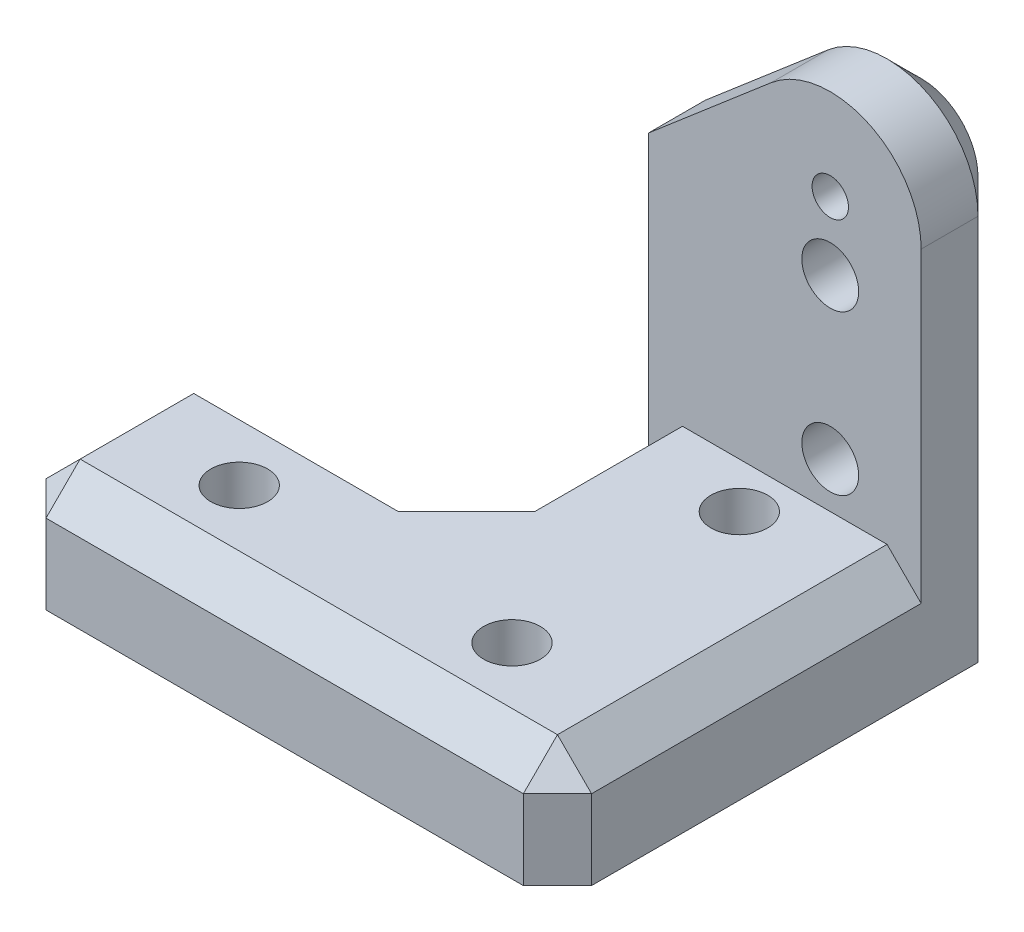
SolidWorks part; units mm, degrees
ref_plane "Plano frontal" through (0, 0, 0) normal (0, 0, 1) x (1, 0, 0)
ref_plane "Plano superior" through (0, 0, 0) normal (0, 1, 0) x (1, 0, 0)
ref_plane "Plano direito" through (0, 0, 0) normal (1, 0, 0) x (0, 0, -1)
sketch "Esboço1" plane through (0, 0, 0) normal (0, 0, 1) x (1, 0, 0)
  line L0 (0, 0) -> (0, 12)
  line L1 (0, 12) -> (9.4001, 20.0398)
  line L4 (16, 17) -> (16, 4)
  line L5 (16, 4) -> (16, 0)
  line L6 (16, 0) -> (0, 0)
  arc A0 (9.4001, 20.0398) -> (16, 17) centre (12, 17) cw
  point P19 (12, 17)
  dimension "D1" = 4
  dimension "D2" = 16
  dimension "D3" = 12
  dimension "D4" = 16
  dimension "D5" = 4
  dimension "D6" = 17
extrude "Ressalto-extrusão1" add sketch "Esboço1" along normal blind 20
sketch "Esboço2" plane through (0, 0, 0) normal (-1, 0, 0) x (0, 0, 1)
  line L0 (0, 0) -> (0, 5) construction
  line L1 (0, 5) -> (20, 5) construction
  line L3 (20, 21) -> (0, 21) construction
  line L4 (20, 5) -> (4, 5)
  line L5 (20, 5) -> (20, 21)
  line L6 (20, 21) -> (4, 21)
  line L7 (4, 5) -> (4, 21)
  dimension "D1" = 16
  dimension "D2" = 5
  dimension "D3" = 4
extrude "Corte-extrusão1" cut sketch "Esboço2" against normal through all
sketch "Esboço4" plane through (0, 0, 4) normal (0, 0, 1) x (1, 0, 0)
  point P0 (12, 17)
hole_wizard "Furo roscado de M21" positions "3DSketch1" profile "Esboço5" tap size "M2" standard "ISO"
sketch3d "3DSketch1"
  point P0 (12, 17, 4)
sketch "Esboço5" plane through (12, 17, 4) normal (1, 0, 0) x (0, -1, 0)
  line L0 (0, 0) -> (0, 6.4807)
  line L1 (0, 6.4807) -> (0.8, 6)
  line L2 (0.8, 6) -> (0.8, 0)
  line L5 (0.8, 0) -> (0, 0)
  line L10 (0, 6.4807) -> (-0.8, 6) construction
  line L11 (0, -6.35) -> (0, 107.95) construction
  dimension "Tap Drill Dia." = 1.6
  dimension "Tap Drill Depth" = 6
  dimension "Drill Angle" = 118
cosmetic thread "Rosca de furo1" parameters "D1"=4, "D2"=2
sketch "Esboço6" plane through (0, 0, 20) normal (0, 0, 1) x (1, 0, 0)
  line L0 (0, 0) -> (4, 0)
  line L1 (0, 0) -> (16, 0) construction
  line L2 (4, 0) -> (4, 15.4212)
  line L3 (0, 12) -> (9.4001, 20.0398) construction
  line L4 (4, 15.4212) -> (0, 12)
  line L5 (0, 12) -> (0, 0)
  dimension "D1" = 4
extrude "Corte-extrusão2" cut sketch "Esboço6" against normal through all
sketch "Esboço9" plane through (4, 0, 0) normal (-1, 0, 0) x (0, 0, 1)
  line L0 (20, 5) -> (12, 5)
  line L1 (4, 5) -> (20, 5) construction
  line L2 (12, 5) -> (12, 0)
  line L3 (0, 0) -> (20, 0) construction
  line L4 (12, 0) -> (20, 0)
  line L5 (20, 0) -> (20, 5)
  dimension "D1" = 8
extrude "Ressalto-extrusão2" add sketch "Esboço9" along normal blind 12
chamfer "Chanfro1" distance 1.5 angle 45 4 edges at (4, 7.7106, 0) (6.7, 17.7305, 0) (13.6734, 20.6332, 0) (16, 8.5, 0)
chamfer "Chanfro2" distance 1.5 angle 45 9 edges at (4, 2.5, 12) (-8, 2.5, 12) (-8, 2.5, 20) (16, 5, 12) (16, 2.5, 20) (4, 5, 20) (-8, 5, 16) (-2, 5, 12) (4, 5, 8)
sketch "Esboço10" plane through (0, 0, 0) normal (0, -1, 0) x (1, 0, 0)
  line L0 (-8, 16) -> (16, 16) construction
  line L1 (-8, 13.5) -> (-8, 18.5) construction
  line L2 (16, 18.5) -> (16, 1.5) construction
  line L3 (10, 0) -> (10, 16) construction
  line L4 (5.5, 0) -> (14.5, 0) construction
  line L5 (10, 16) -> (10, 20) construction
  line L6 (-6.5, 20) -> (14.5, 20) construction
  point P10 (10, 6)
  point P14 (10, 11)
  point P15 (-2, 16)
  point P16 (4, 16)
  dimension "D1" = 5
  dimension "D2" = 5
  dimension "D3" = 6
  dimension "D4" = 6
hole_wizard "Furo roscado de M31" positions "3DSketch2" profile "Esboço11" tap size "M3" standard "ISO"
sketch3d "3DSketch2"
  point P0 (10, 0, 6)
  point P6 (10, 0, 16)
  point P12 (-2, 0, 16)
sketch "Esboço11" plane through (10, 0, 6) normal (1, 0, 0) x (0, 0, -1)
  line L0 (0, 0) -> (0, 9.2511)
  line L1 (0, 9.2511) -> (1.25, 8.5)
  line L2 (1.25, 8.5) -> (1.25, 0)
  line L5 (1.25, 0) -> (0, 0)
  line L10 (0, 9.2511) -> (-1.25, 8.5) construction
  line L11 (0, -6.35) -> (0, 107.95) construction
  dimension "Tap Drill Dia." = 2.5
  dimension "Tap Drill Depth" = 8.5
  dimension "Drill Angle" = 118
cosmetic thread "Rosca de furo2" parameters "D1"=5, "D2"=3
cosmetic thread "Rosca de furo4" parameters "D1"=5, "D2"=3
cosmetic thread "Rosca de furo6" parameters "D1"=5, "D2"=3
sketch "Esboço12" plane through (0, 0, 0) normal (0, 0, -1) x (-1, 0, 0)
  line L0 (-16, 0) -> (-16, 17) construction
  line L1 (-5.5, 0) -> (-14.5, 0) construction
  line L2 (-12, 7) -> (-12, 14) construction
  point P0 (-12, 7)
  dimension "D1" = 4
  dimension "D2" = 7
  dimension "D3" = 7
hole_wizard "Broca de rosquear para tarraxa de M31" positions "3DSketch3" profile "Esboço13" hole size "M3" standard "ISO" end condition up to next
sketch3d "3DSketch3"
  point P0 (12, 7, 0)
  point P3 (12, 14, 0)
sketch "Esboço13" plane through (12, 7, 0) normal (1, 0, 0) x (0, 1, 0)
  line L0 (0, 0) -> (0, 4)
  line L1 (0, 4) -> (1.25, 4)
  line L2 (1.25, 4) -> (1.25, 0)
  line L5 (1.25, 0) -> (0, 0)
  line L11 (0, -6.35) -> (0, 107.95) construction
  dimension "Thru Hole Dia." = 2.5
  dimension "Thru Hole Depth" = 4
